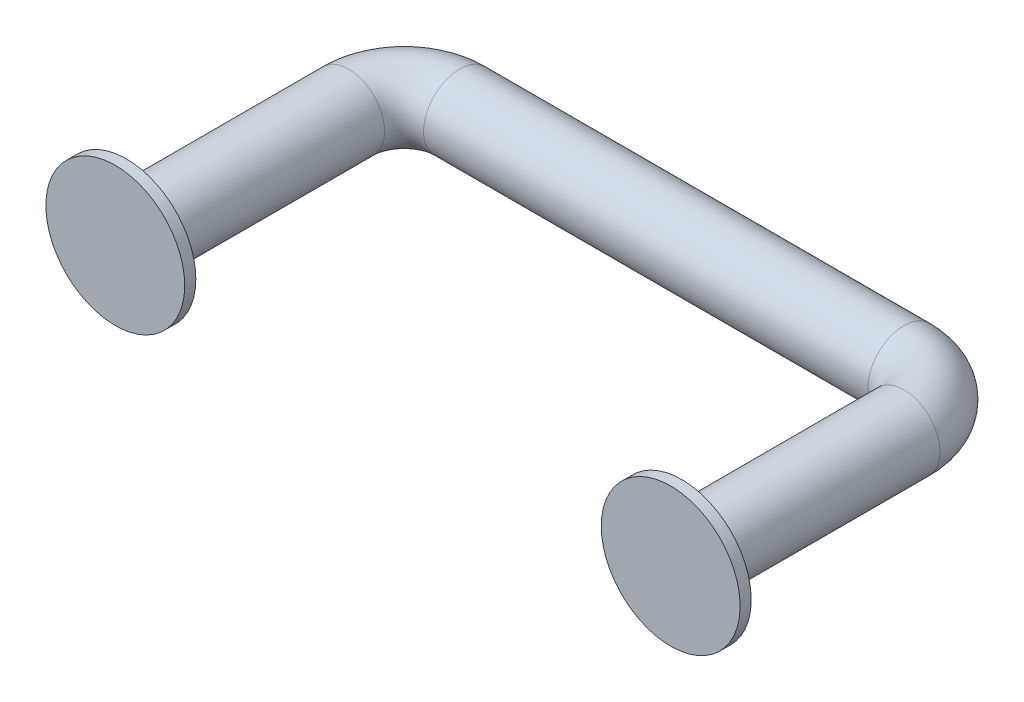
SolidWorks part; units mm, degrees
ref_plane "Plan de face" through (0, 0, 0) normal (0, 0, 1) x (1, 0, 0)
ref_plane "Plan de dessus" through (0, 0, 0) normal (0, 1, 0) x (1, 0, 0)
ref_plane "Plan de droite" through (0, 0, 0) normal (1, 0, 0) x (0, 0, -1)
sketch "Esquisse1" plane through (0, 0, 0) normal (0, 1, 0) x (1, 0, 0)
  line L0 (-40, 0) -> (40, 0)
  line L1 (50, -10) -> (50, -48.8189)
  line L2 (-50, -10) -> (-50, -50)
  arc A0 (40, 0) -> (50, -10) centre (40, -10) cw
  arc A1 (-50, -10) -> (-40, 0) centre (-40, -10) cw
  point P7 (50, 0)
  point P10 (-50, 0)
  dimension "D3" = 10
  dimension "D1" = 100
  dimension "D2" = 50
sweep "Balayage2" add path "Esquisse1" circular profile diameter 13 parameters "D3"=13
sketch "Esquisse15" plane through (0, 0, 0) normal (0, 0, 1) x (1, 0, 0)
  line L0 (0, 28.2413) -> (0, -31.8389) construction
  circle A0 centre (-50, 0) radius 12.5
  circle A1 centre (50, 0) radius 12.5
  dimension "D1" = 25
extrude "Boss.-Extru.1" add sketch "Esquisse15" along normal blind 2 from offset 50
